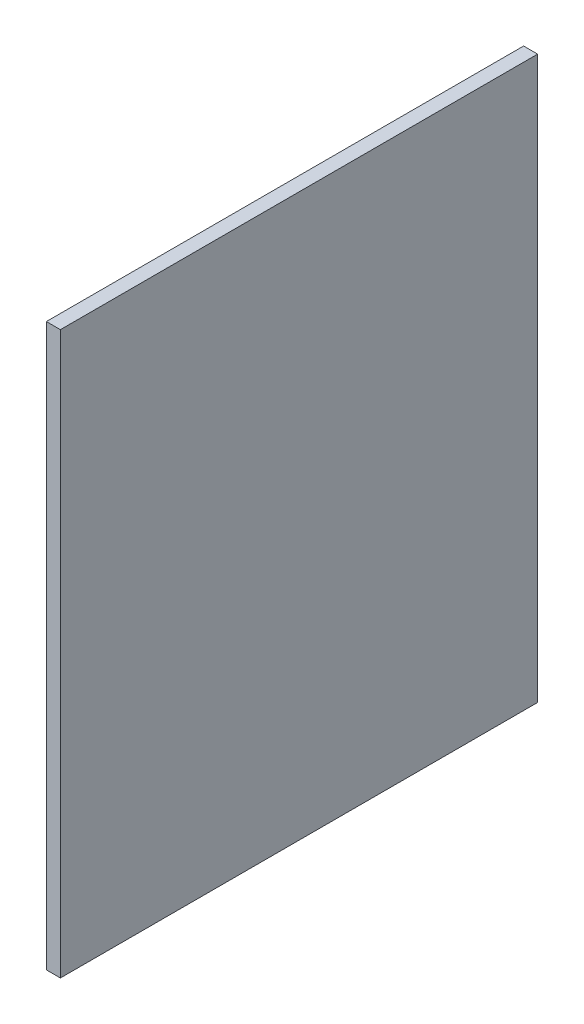
SolidWorks part; units mm, degrees
material "Fundición gris (SN)"
ref_plane "Alzado" through (0, 0, 0) normal (0, 0, 1) x (1, 0, 0)
ref_plane "Planta" through (0, 0, 0) normal (0, 1, 0) x (1, 0, 0)
ref_plane "Vista lateral" through (0, 0, 0) normal (1, 0, 0) x (0, 0, -1)
sketch "Croquis1" plane through (0, 0, 0) normal (1, 0, 0) x (0, 0, -1)
  line L1 (85, -100) -> (-85, -100)
  line L2 (85, -100) -> (85, 100)
  line L3 (85, 100) -> (-85, 100)
  line L4 (-85, -100) -> (-85, 100)
  line L5 (85, -100) -> (-85, 100) construction
  line L6 (85, 100) -> (-85, -100) construction
  point P0 (0, 0)
  dimension "D1" = 170
  dimension "D2" = 200
extrude "Saliente-Extruir1" add sketch "Croquis1" along normal blind 5
